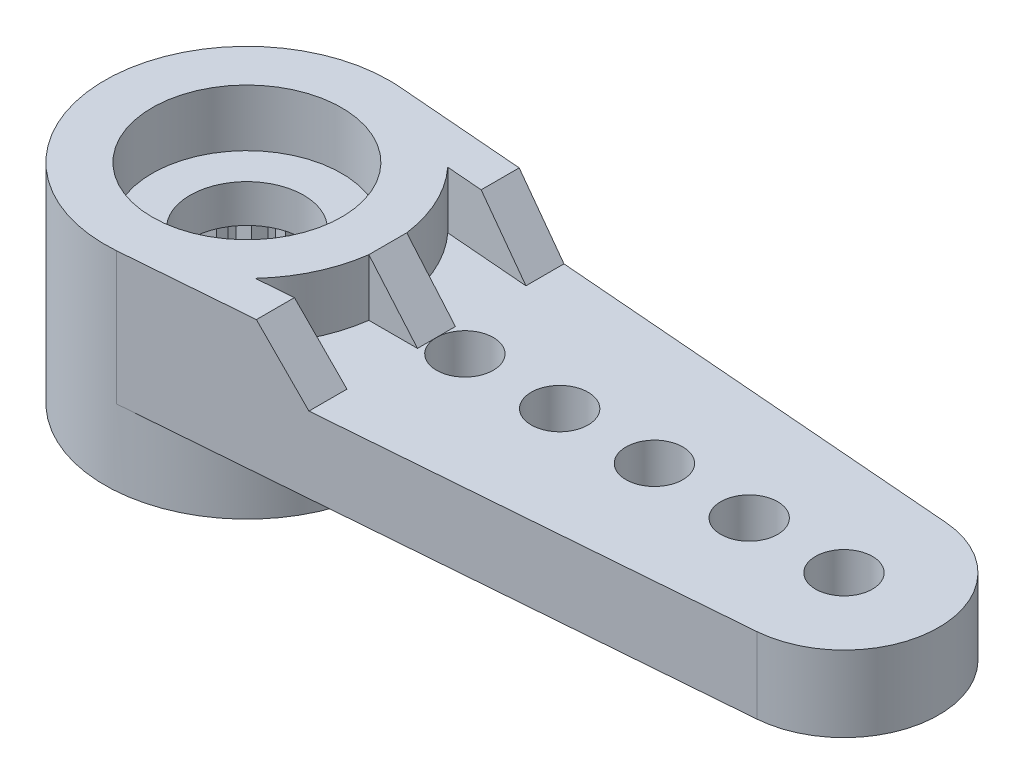
SolidWorks part; units mm, degrees
ref_plane "Plano frontal" through (0, 0, 0) normal (0, 0, 1) x (1, 0, 0)
ref_plane "Plano superior" through (0, 0, 0) normal (0, 1, 0) x (1, 0, 0)
ref_plane "Plano direito" through (0, 0, 0) normal (1, 0, 0) x (0, 0, -1)
sketch "Esboço1" plane through (0, 0, 0) normal (0, 1, 0) x (1, 0, 0)
  line L0 (0, 0) -> (15.75, 0) construction
  line L1 (-3.75, 0) -> (18.25, 0) construction
  line L2 (0.2976, 3.7382) -> (15.9484, 2.4921)
  line L3 (0.2976, -3.7382) -> (15.9484, -2.4921)
  arc A0 (0.2976, 3.7382) -> (0.2976, -3.7382) centre (0, 0) ccw
  arc A1 (15.9484, -2.4921) -> (15.9484, 2.4921) centre (15.75, 0) ccw
  circle A2 centre (15.75, 0) radius 0.75
  circle A3 centre (0, 0) radius 1.5
  circle A4 centre (13.25, 0) radius 0.75
  circle A5 centre (10.75, 0) radius 0.75
  circle A6 centre (8.25, 0) radius 0.75
  circle A7 centre (5.75, 0) radius 0.75
  dimension "D1" = 7.5
  dimension "D2" = 5
  dimension "D4" = 3
  dimension "D5" = 1.5
  dimension "D3" = 22
  dimension "D7" = 10
  dimension "D6" = 5
extrude "Ressalto-extrusão1" add sketch "Esboço1" along normal blind 2
sketch "Esboço3" plane through (0, 2, 0) normal (0, 1, 0) x (1, 0, 0)
  circle A0 centre (0, 0) radius 2.5
  circle A1 centre (0, 0) radius 3.75
  arc A2 (0.2976, 3.7382) -> (0.2976, -3.7382) centre (0, 0) ccw construction
  dimension "D1" = 5
extrude "Ressalto-extrusão2" add sketch "Esboço3" along normal blind 1.5
sketch "Esboço5" plane through (0, 2, 0) normal (0, 1, 0) x (1, 0, 0)
  line L0 (15.9484, 2.4921) -> (0.2976, 3.7382) construction
  line L1 (5, 3.3638) -> (0.2976, 3.7382)
  line L3 (5, -2.3606) -> (5, -3.3638)
  line L4 (3.7165, 0) -> (0, 0) construction
  line L5 (3.7165, 0.5) -> (5, 0.5)
  line L6 (3.7165, 0.5) -> (3.7165, -0.5)
  line L7 (3.7165, -0.5) -> (5, -0.5)
  line L8 (5, 0.5) -> (5, -0.5)
  line L9 (5, 2.3606) -> (2.7597, 2.539)
  line L10 (5, 2.3606) -> (5, 3.3638)
  line L11 (5, -2.3606) -> (2.7597, -2.539)
  line L12 (5, -3.3638) -> (0.2976, -3.7382)
  circle A0 centre (0, 0) radius 3.75 construction
  arc A1 (2.7597, 2.539) -> (0.2976, 3.7382) centre (0, 0) ccw
  circle A2 centre (5.75, 0) radius 0.75 construction
  arc A3 (0.2976, -3.7382) -> (0.2976, 3.7382) centre (0, 0) ccw construction
  arc A4 (3.7165, -0.5) -> (3.7165, 0.5) centre (0, 0) ccw
  arc A5 (2.7597, -2.539) -> (0.2976, -3.7382) centre (0, 0) cw
  arc M8 (0.2976, 3.7382) -> (0.2976, -3.7382) centre (0, 0) cw
  line M9 (0.2976, -3.7382) -> (15.9484, -2.4921)
  line M11 (15.9484, 2.4921) -> (0.2976, 3.7382)
  dimension "D1" = 1
  dimension "D2" = 1
extrude "Ressalto-extrusão3" add sketch "Esboço5" along normal up to surface (1.5 mm away) contours L9 L10 M11 M8 | L8 L5 L7 M8 | L3 L11 M8 M9 up to face at (0, 3.5, 3.75)
sketch "Esboço6" plane through (0, 0, 0) normal (0, 0, 1) x (1, 0, 0)
  line L0 (3.7165, 3.5) -> (5, 2)
  line L1 (5, 2) -> (5, 3.5)
  line L2 (5, 3.5) -> (3.7165, 3.5)
extrude "Corte-extrusão1" cut sketch "Esboço6" against normal through all and the other way through all
sketch "Esboço7" plane through (0, 0, 0) normal (0, -1, 0) x (1, 0, 0)
  circle A0 centre (0, 0) radius 3.75
  arc A1 (0.2976, 3.7382) -> (0.2976, -3.7382) centre (0, 0) ccw construction
  circle A2 centre (0, 0) radius 1.5 construction
  circle A3 centre (0, 0) radius 1.5
extrude "Ressalto-extrusão4" add sketch "Esboço7" along normal blind 2
sketch "Esboço8" plane through (0, -2, 0) normal (0, -1, 0) x (1, 0, 0)
  circle A0 centre (0, 0) radius 2.5
  dimension "D1" = 5
extrude "Corte-extrusão2" cut sketch "Esboço8" against normal blind 3
sketch "Esboço9" plane through (0, 1, 0) normal (0, -1, 0) x (1, 0, 0)
  line L0 (-0.3, 2.4819) -> (0, 2.1819)
  line L1 (0, 2.1819) -> (0.3, 2.4819)
  line L2 (0.3, 2.4819) -> (-0.3, 2.4819) construction
  line L3 (0, 2.1819) -> (0, 0) construction
  line L4 (0.4449, 2.4601) -> (0.6431, 2.085)
  line L5 (0.6431, 2.085) -> (1.0182, 2.2832)
  line L6 (1.0182, 2.2832) -> (0.4449, 2.4601) construction
  line L7 (1.1503, 2.2197) -> (1.2291, 1.8028)
  line L8 (1.2291, 1.8028) -> (1.646, 1.8817)
  line L9 (1.646, 1.8817) -> (1.1503, 2.2197) construction
  line L10 (1.7534, 1.782) -> (1.7059, 1.3604)
  line L11 (1.7059, 1.3604) -> (2.1275, 1.3129)
  line L12 (2.1275, 1.3129) -> (1.7534, 1.782) construction
  line L13 (2.2008, 1.186) -> (2.0311, 0.7972)
  line L14 (2.0311, 0.7972) -> (2.42, 0.6275)
  line L15 (2.42, 0.6275) -> (2.2008, 1.186) construction
  line L16 (2.4526, 0.4846) -> (2.1758, 0.1631)
  line L17 (2.1758, 0.1631) -> (2.4974, -0.1137)
  line L18 (2.4974, -0.1137) -> (2.4526, 0.4846) construction
  line L19 (2.4865, -0.2598) -> (2.1272, -0.4855)
  line L20 (2.1272, -0.4855) -> (2.353, -0.8448)
  line L21 (2.353, -0.8448) -> (2.4865, -0.2598) construction
  line L22 (2.2994, -0.9812) -> (1.8896, -1.091)
  line L23 (1.8896, -1.091) -> (1.9994, -1.5008)
  line L24 (1.9994, -1.5008) -> (2.2994, -0.9812) construction
  line L25 (1.9081, -1.6153) -> (1.4841, -1.5995)
  line L26 (1.4841, -1.5995) -> (1.4682, -2.0234)
  line L27 (1.4682, -2.0234) -> (1.9081, -1.6153) construction
  line L28 (1.3472, -2.106) -> (0.9467, -1.9659)
  line L29 (0.9467, -1.9659) -> (0.8066, -2.3663)
  line L30 (0.8066, -2.3663) -> (1.3472, -2.106) construction
  line L31 (0.6666, -2.4095) -> (0.3252, -2.1576)
  line L32 (0.3252, -2.1576) -> (0.0733, -2.4989)
  line L33 (0.0733, -2.4989) -> (0.6666, -2.4095) construction
  line L34 (-0.0733, -2.4989) -> (-0.3252, -2.1576)
  line L35 (-0.3252, -2.1576) -> (-0.6666, -2.4095)
  line L36 (-0.6666, -2.4095) -> (-0.0733, -2.4989) construction
  line L37 (-0.8066, -2.3663) -> (-0.9467, -1.9659)
  line L38 (-0.9467, -1.9659) -> (-1.3472, -2.106)
  line L39 (-1.3472, -2.106) -> (-0.8066, -2.3663) construction
  line L40 (-1.4682, -2.0234) -> (-1.4841, -1.5995)
  line L41 (-1.4841, -1.5995) -> (-1.9081, -1.6153)
  line L42 (-1.9081, -1.6153) -> (-1.4682, -2.0234) construction
  line L43 (-1.9994, -1.5008) -> (-1.8896, -1.091)
  line L44 (-1.8896, -1.091) -> (-2.2994, -0.9812)
  line L45 (-2.2994, -0.9812) -> (-1.9994, -1.5008) construction
  line L46 (-2.353, -0.8448) -> (-2.1272, -0.4855)
  line L47 (-2.1272, -0.4855) -> (-2.4865, -0.2598)
  line L48 (-2.4865, -0.2598) -> (-2.353, -0.8448) construction
  line L49 (-2.4974, -0.1137) -> (-2.1758, 0.1631)
  line L50 (-2.1758, 0.1631) -> (-2.4526, 0.4846)
  line L51 (-2.4526, 0.4846) -> (-2.4974, -0.1137) construction
  line L52 (-2.42, 0.6275) -> (-2.0311, 0.7972)
  line L53 (-2.0311, 0.7972) -> (-2.2008, 1.186)
  line L54 (-2.2008, 1.186) -> (-2.42, 0.6275) construction
  line L55 (-2.1275, 1.3129) -> (-1.7059, 1.3604)
  line L56 (-1.7059, 1.3604) -> (-1.7534, 1.782)
  line L57 (-1.7534, 1.782) -> (-2.1275, 1.3129) construction
  line L58 (-1.646, 1.8817) -> (-1.2291, 1.8028)
  line L59 (-1.2291, 1.8028) -> (-1.1503, 2.2197)
  line L60 (-1.1503, 2.2197) -> (-1.646, 1.8817) construction
  line L61 (-1.0182, 2.2832) -> (-0.6431, 2.085)
  line L62 (-0.6431, 2.085) -> (-0.4449, 2.4601)
  line L63 (-0.4449, 2.4601) -> (-1.0182, 2.2832) construction
  circle A0 centre (0, 0) radius 2.5 construction
  arc A1 (0.3, 2.4819) -> (-0.3, 2.4819) centre (0, 0) ccw
  arc A2 (1.0182, 2.2832) -> (0.4449, 2.4601) centre (0, 0) ccw
  arc A3 (1.646, 1.8817) -> (1.1503, 2.2197) centre (0, 0) ccw
  arc A4 (2.1275, 1.3129) -> (1.7534, 1.782) centre (0, 0) ccw
  arc A5 (2.42, 0.6275) -> (2.2008, 1.186) centre (0, 0) ccw
  arc A6 (2.4974, -0.1137) -> (2.4526, 0.4846) centre (0, 0) ccw
  arc A7 (2.353, -0.8448) -> (2.4865, -0.2598) centre (0, 0) ccw
  arc A8 (1.9994, -1.5008) -> (2.2994, -0.9812) centre (0, 0) ccw
  arc A9 (1.4682, -2.0234) -> (1.9081, -1.6153) centre (0, 0) ccw
  arc A10 (0.8066, -2.3663) -> (1.3472, -2.106) centre (0, 0) ccw
  arc A11 (0.0733, -2.4989) -> (0.6666, -2.4095) centre (0, 0) ccw
  arc A12 (-0.6666, -2.4095) -> (-0.0733, -2.4989) centre (0, 0) ccw
  arc A13 (-1.3472, -2.106) -> (-0.8066, -2.3663) centre (0, 0) ccw
  arc A14 (-1.9081, -1.6153) -> (-1.4682, -2.0234) centre (0, 0) ccw
  arc A15 (-2.2994, -0.9812) -> (-1.9994, -1.5008) centre (0, 0) ccw
  arc A16 (-2.4865, -0.2598) -> (-2.353, -0.8448) centre (0, 0) ccw
  arc A17 (-2.4526, 0.4846) -> (-2.4974, -0.1137) centre (0, 0) ccw
  arc A18 (-2.2008, 1.186) -> (-2.42, 0.6275) centre (0, 0) ccw
  arc A19 (-1.7534, 1.782) -> (-2.1275, 1.3129) centre (0, 0) ccw
  arc A20 (-1.1503, 2.2197) -> (-1.646, 1.8817) centre (0, 0) ccw
  arc A21 (-0.4449, 2.4601) -> (-1.0182, 2.2832) centre (0, 0) ccw
  point P68 (0, 0)
  dimension "D1" = 90
  dimension "D2" = 0.3
  dimension "D3" = 21
extrude "Ressalto-extrusão5" add sketch "Esboço9" along normal up to surface (3 mm away) up to face at (0, -2, -2.5)
